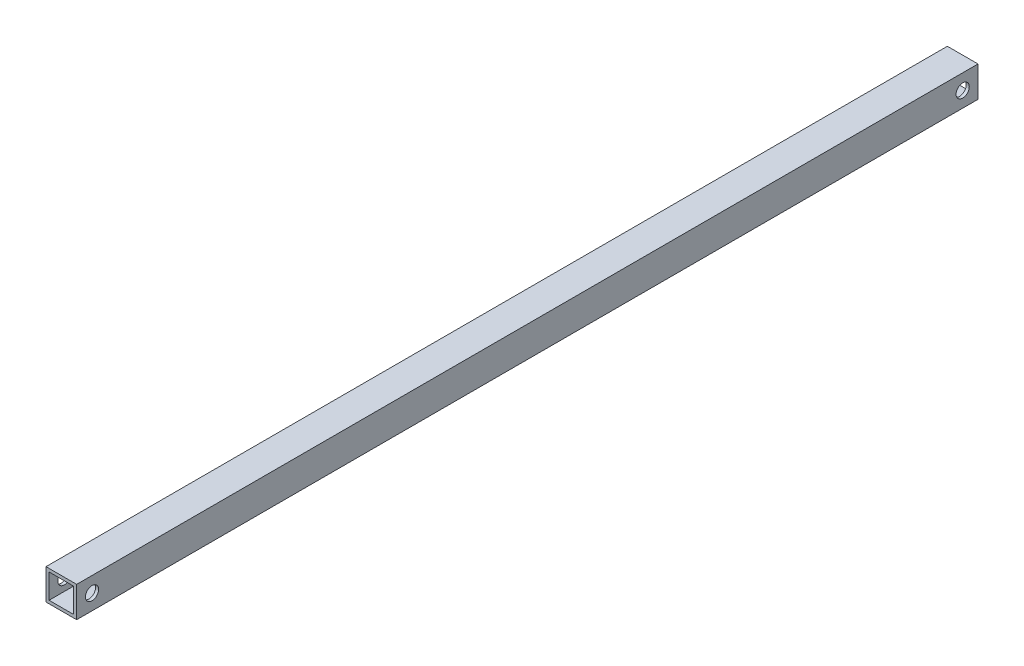
SolidWorks part; units mm, degrees
material "5052-H34"
ref_plane "正面" through (0, 0, 0) normal (0, 0, 1) x (1, 0, 0)
ref_plane "平面" through (0, 0, 0) normal (0, 1, 0) x (1, 0, 0)
ref_plane "右側面" through (0, 0, 0) normal (1, 0, 0) x (0, 0, -1)
sketch "ｽｹｯﾁ1" plane through (0, 0, 0) normal (0, 0, 1) x (1, 0, 0)
  line L1 (-5, 5) -> (5, 5)
  line L2 (-5, 5) -> (-5, -5)
  line L3 (-5, -5) -> (5, -5)
  line L4 (5, 5) -> (5, -5)
  line L5 (-5, 5) -> (5, -5) construction
  line L6 (-5, -5) -> (5, 5) construction
  point P0 (0, 0)
  dimension "D1" = 10
  dimension "D2" = 10
extrude "押し出し-薄板1" add sketch "ｽｹｯﾁ1" along normal blind 294 thin
sketch "ｽｹｯﾁ2" plane through (5, 0, 0) normal (1, 0, 0) x (0, 0, -1)
  line L0 (-147, 5) -> (-147, -5) construction
  line L1 (-294, 5) -> (0, 5) construction
  line L2 (-294, -5) -> (0, -5) construction
  line L3 (0, 0) -> (-5, 0) construction
  circle A0 centre (-5, 0) radius 2.15
  circle A1 centre (-289, 0) radius 2.15
  dimension "D1" = 4.3
  dimension "D2" = 5
extrude "ｶｯﾄ - 押し出し1" cut sketch "ｽｹｯﾁ2" against normal through all
